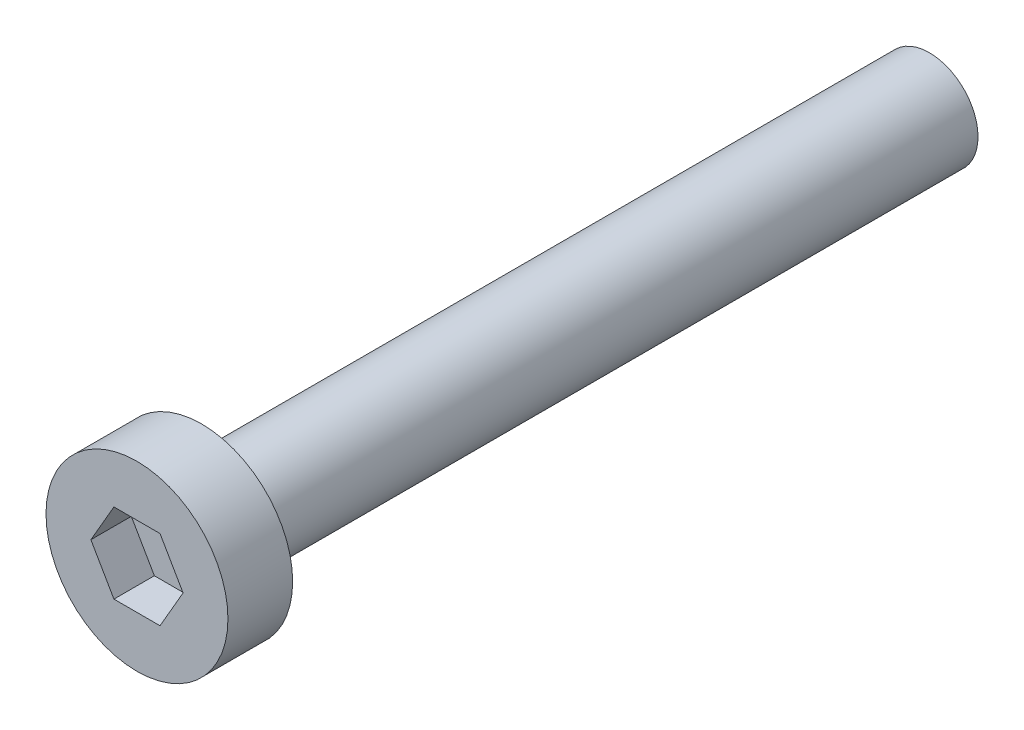
SolidWorks part; units mm, degrees
ref_plane "Plano frontal" through (0, 0, 0) normal (0, 0, 1) x (1, 0, 0)
ref_plane "Plano superior" through (0, 0, 0) normal (0, 1, 0) x (1, 0, 0)
ref_plane "Plano direito" through (0, 0, 0) normal (1, 0, 0) x (0, 0, -1)
sketch "Esboço1" plane through (0, 0, 0) normal (0, 0, 1) x (1, 0, 0)
  circle A0 centre (0, 0) radius 5.625
  dimension "D1" = 11.25
extrude "Ressalto-extrusão1" add sketch "Esboço1" along normal blind 4
sketch "Esboço2" plane through (0, 0, 4) normal (0, 0, 1) x (1, 0, 0)
  line L1 (2.85, 0) -> (1.425, 2.4682)
  line L2 (1.425, 2.4682) -> (-1.425, 2.4682)
  line L3 (-1.425, 2.4682) -> (-2.85, 0)
  line L4 (-2.85, 0) -> (-1.425, -2.4682)
  line L5 (-1.425, -2.4682) -> (1.425, -2.4682)
  line L6 (1.425, -2.4682) -> (2.85, 0)
  circle A0 centre (0, 0) radius 2.4682 construction
  dimension "D1" = 5.7
extrude "Corte-extrusão1" cut sketch "Esboço2" against normal blind 2.5
sketch "Esboço3" plane through (0, 0, 0) normal (0, 0, -1) x (-1, 0, 0)
  circle A0 centre (0, 0) radius 3
  dimension "D1" = 6
extrude "Ressalto-extrusão2" add sketch "Esboço3" along normal blind 45
